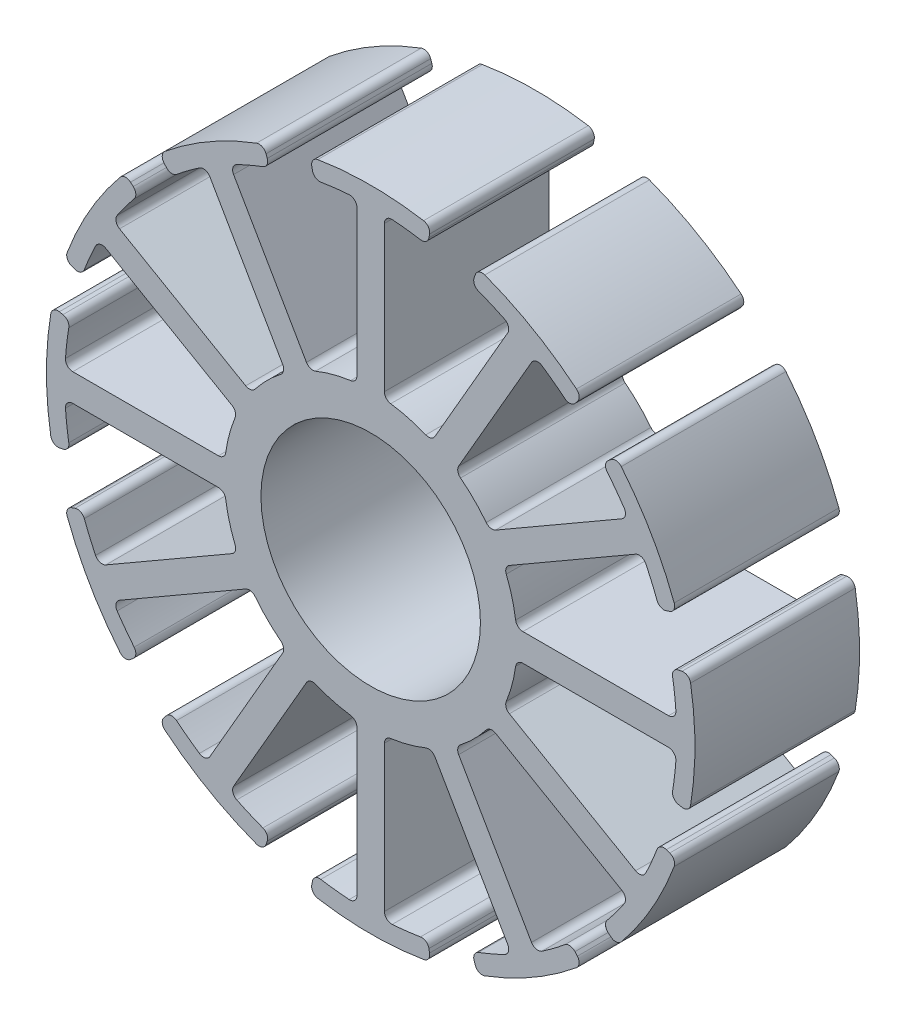
SolidWorks part; units mm, degrees
material "Alloy Steel"
ref_plane "Front Plane" through (0, 0, 0) normal (0, 0, 1) x (1, 0, 0)
ref_plane "Top Plane" through (0, 0, 0) normal (0, 1, 0) x (1, 0, 0)
ref_plane "Right Plane" through (0, 0, 0) normal (1, 0, 0) x (0, 0, -1)
sketch "Sketch1" plane through (0, 0, 0) normal (0, 0, 1) x (1, 0, 0)
  line L0 (-16.4335, 3.1092) -> (-17.416, 3.2951)
  line L1 (-16.4335, -3.1092) -> (-17.416, -3.2951)
  line L2 (-16.725, 0) -> (0, 0) construction
  line L3 (-16.7082, -0.75) -> (-7.9648, -0.75)
  line L4 (-16.7082, 0.75) -> (-7.9648, 0.75)
  line L5 (-12.6772, 10.9094) -> (-13.4351, 11.5617)
  line L6 (-15.7864, 5.524) -> (-16.7303, 5.8543)
  line L7 (-14.8447, 7.7046) -> (-7.2727, 3.3329)
  line L8 (-14.0947, 9.0036) -> (-6.5227, 4.6319)
  line L9 (-5.524, 15.7864) -> (-5.8543, 16.7303)
  line L10 (-10.9094, 12.6772) -> (-11.5617, 13.4351)
  line L11 (-9.0036, 14.0947) -> (-4.6319, 6.5227)
  line L12 (-7.7046, 14.8447) -> (-3.3329, 7.2727)
  line L13 (3.1092, 16.4335) -> (3.2951, 17.416)
  line L14 (-3.1092, 16.4335) -> (-3.2951, 17.416)
  line L15 (-0.75, 16.7082) -> (-0.75, 7.9648)
  line L16 (0.75, 16.7082) -> (0.75, 7.9648)
  line L17 (10.9094, 12.6772) -> (11.5617, 13.4351)
  line L18 (5.524, 15.7864) -> (5.8543, 16.7303)
  line L19 (7.7046, 14.8447) -> (3.3329, 7.2727)
  line L20 (9.0036, 14.0947) -> (4.6319, 6.5227)
  line L21 (15.7864, 5.524) -> (16.7303, 5.8543)
  line L22 (12.6772, 10.9094) -> (13.4351, 11.5617)
  line L23 (14.0947, 9.0036) -> (6.5227, 4.6319)
  line L24 (14.8447, 7.7046) -> (7.2727, 3.3329)
  line L25 (16.4335, -3.1092) -> (17.416, -3.2951)
  line L26 (16.4335, 3.1092) -> (17.416, 3.2951)
  line L27 (16.7082, 0.75) -> (7.9648, 0.75)
  line L28 (16.7082, -0.75) -> (7.9648, -0.75)
  line L29 (12.6772, -10.9094) -> (13.4351, -11.5617)
  line L30 (15.7864, -5.524) -> (16.7303, -5.8543)
  line L31 (14.8447, -7.7046) -> (7.2727, -3.3329)
  line L32 (14.0947, -9.0036) -> (6.5227, -4.6319)
  line L33 (5.524, -15.7864) -> (5.8543, -16.7303)
  line L34 (10.9094, -12.6772) -> (11.5617, -13.4351)
  line L35 (9.0036, -14.0947) -> (4.6319, -6.5227)
  line L36 (7.7046, -14.8447) -> (3.3329, -7.2727)
  line L37 (-3.1092, -16.4335) -> (-3.2951, -17.416)
  line L38 (3.1092, -16.4335) -> (3.2951, -17.416)
  line L39 (0.75, -16.7082) -> (0.75, -7.9648)
  line L40 (-0.75, -16.7082) -> (-0.75, -7.9648)
  line L41 (-10.9094, -12.6772) -> (-11.5617, -13.4351)
  line L42 (-5.524, -15.7864) -> (-5.8543, -16.7303)
  line L43 (-7.7046, -14.8447) -> (-3.3329, -7.2727)
  line L44 (-9.0036, -14.0947) -> (-4.6319, -6.5227)
  line L45 (-15.7864, -5.524) -> (-16.7303, -5.8543)
  line L46 (-12.6772, -10.9094) -> (-13.4351, -11.5617)
  line L47 (-14.0947, -9.0036) -> (-6.5227, -4.6319)
  line L48 (-14.8447, -7.7046) -> (-7.2727, -3.3329)
  circle A0 centre (0, 0) radius 6 construction
  circle A1 centre (0, 0) radius 6
  circle A2 centre (0, 0) radius 17.725
  arc A3 (-17.7173, 1.9566) -> (-17.4682, -3.5487) centre (0, 0) ccw construction
  arc A4 (-16.4335, 3.1092) -> (-16.4335, -3.1092) centre (0, 0) ccw
  circle A5 centre (0, 0) radius 8
  arc A6 (-12.6772, 10.9094) -> (-15.7864, 5.524) centre (0, 0) ccw
  arc A7 (-5.524, 15.7864) -> (-10.9094, 12.6772) centre (0, 0) ccw
  arc A8 (3.1092, 16.4335) -> (-3.1092, 16.4335) centre (0, 0) ccw
  arc A9 (10.9094, 12.6772) -> (5.524, 15.7864) centre (0, 0) ccw
  arc A10 (15.7864, 5.524) -> (12.6772, 10.9094) centre (0, 0) ccw
  arc A11 (16.4335, -3.1092) -> (16.4335, 3.1092) centre (0, 0) ccw
  arc A12 (12.6772, -10.9094) -> (15.7864, -5.524) centre (0, 0) ccw
  arc A13 (5.524, -15.7864) -> (10.9094, -12.6772) centre (0, 0) ccw
  arc A14 (-3.1092, -16.4335) -> (3.1092, -16.4335) centre (0, 0) ccw
  arc A15 (-10.9094, -12.6772) -> (-5.524, -15.7864) centre (0, 0) ccw
  arc A16 (-15.7864, -5.524) -> (-12.6772, -10.9094) centre (0, 0) ccw
  point P12 (-16.725, 0)
  point P109 (0, 0)
  dimension "D1" = 0.1
  dimension "D2" = 1
  dimension "D3" = 1.5
  dimension "D6" = 2.5
  dimension "D4" = 2
  dimension "D5" = 12
extrude "Boss-Extrude1" add sketch "Sketch1" along normal up to surface (9 mm away)
fillet "Fillet1" radius 0.4 96 edges at (-16.4335, -3.1092, 4.5) (-17.416, -3.2951, 4.5) (-17.416, 3.2951, 4.5) (-16.4335, 3.1092, 4.5) (-16.7082, 0.75, 4.5) (-7.9648, 0.75, 4.5) (-7.2727, 3.3329, 4.5) (-14.8447, 7.7046, 4.5) (-15.7864, 5.524, 4.5) (-16.7303, 5.8543, 4.5) (-13.4351, 11.5617, 4.5) (-12.6772, 10.9094, 4.5) (-14.0947, 9.0036, 4.5) (-6.5227, 4.6319, 4.5) (-4.6319, 6.5227, 4.5) (-9.0036, 14.0947, 4.5) (-10.9094, 12.6772, 4.5) (-11.5617, 13.4351, 4.5) (-5.8543, 16.7303, 4.5) (-5.524, 15.7864, 4.5) (-7.7046, 14.8447, 4.5) (-3.3329, 7.2727, 4.5) (-0.75, 7.9648, 4.5) (-0.75, 16.7082, 4.5) (-3.1092, 16.4335, 4.5) (-3.2951, 17.416, 4.5) (3.2951, 17.416, 4.5) (3.1092, 16.4335, 4.5) (0.75, 16.7082, 4.5) (0.75, 7.9648, 4.5) (3.3329, 7.2727, 4.5) (7.7046, 14.8447, 4.5) (5.524, 15.7864, 4.5) (5.8543, 16.7303, 4.5) (11.5617, 13.4351, 4.5) (10.9094, 12.6772, 4.5) (9.0036, 14.0947, 4.5) (4.6319, 6.5227, 4.5) (6.5227, 4.6319, 4.5) (14.0947, 9.0036, 4.5) (12.6772, 10.9094, 4.5) (13.4351, 11.5617, 4.5) (16.7303, 5.8543, 4.5) (15.7864, 5.524, 4.5) (14.8447, 7.7046, 4.5) (7.2727, 3.3329, 4.5) (7.9648, 0.75, 4.5) (16.7082, 0.75, 4.5) (16.4335, 3.1092, 4.5) (17.416, 3.2951, 4.5) (17.416, -3.2951, 4.5) (16.4335, -3.1092, 4.5) (16.7082, -0.75, 4.5) (7.9648, -0.75, 4.5) (7.2727, -3.3329, 4.5) (14.8447, -7.7046, 4.5) (15.7864, -5.524, 4.5) (16.7303, -5.8543, 4.5) (13.4351, -11.5617, 4.5) (12.6772, -10.9094, 4.5) (14.0947, -9.0036, 4.5) (6.5227, -4.6319, 4.5) (4.6319, -6.5227, 4.5) (9.0036, -14.0947, 4.5) (10.9094, -12.6772, 4.5) (11.5617, -13.4351, 4.5) (5.8543, -16.7303, 4.5) (5.524, -15.7864, 4.5) (7.7046, -14.8447, 4.5) (3.3329, -7.2727, 4.5) (0.75, -7.9648, 4.5) (0.75, -16.7082, 4.5) (3.1092, -16.4335, 4.5) (3.2951, -17.416, 4.5) (-3.1092, -16.4335, 4.5) (-0.75, -16.7082, 4.5) (-0.75, -7.9648, 4.5) (-3.3329, -7.2727, 4.5) (-7.7046, -14.8447, 4.5) (-5.524, -15.7864, 4.5) (-5.8543, -16.7303, 4.5) (-11.5617, -13.4351, 4.5) (-10.9094, -12.6772, 4.5) (-9.0036, -14.0947, 4.5) (-4.6319, -6.5227, 4.5) (-6.5227, -4.6319, 4.5) (-14.0947, -9.0036, 4.5) (-12.6772, -10.9094, 4.5) (-13.4351, -11.5617, 4.5) (-16.7303, -5.8543, 4.5) (-15.7864, -5.524, 4.5) (-14.8447, -7.7046, 4.5) (-7.2727, -3.3329, 4.5) (-7.9648, -0.75, 4.5) (-16.7082, -0.75, 4.5) (-3.2951, -17.416, 4.5)
